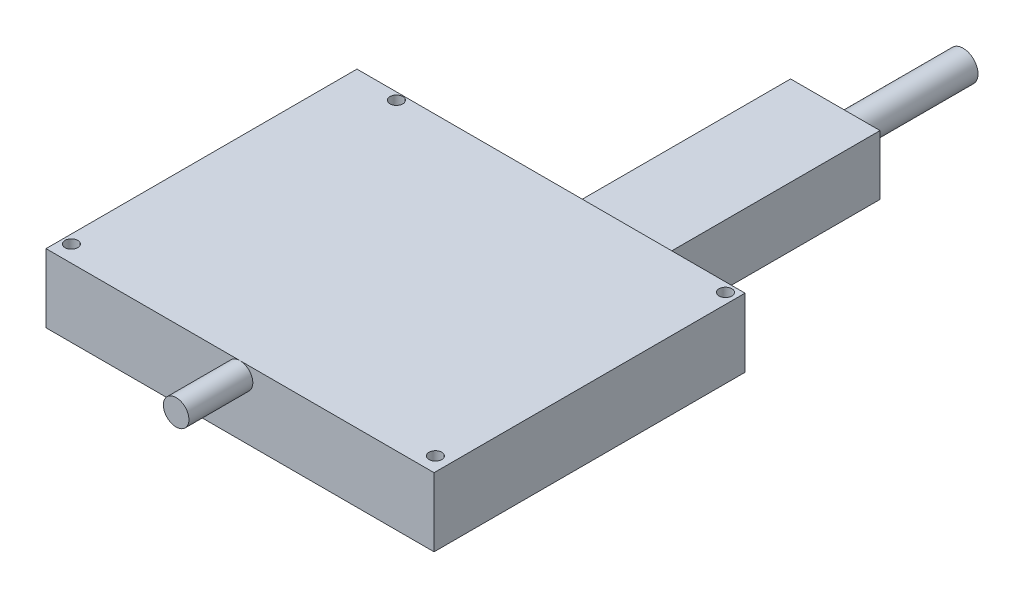
SolidWorks part; units mm, degrees
ref_plane "Front Plane" through (0, 0, 0) normal (0, 0, 1) x (1, 0, 0)
ref_plane "Top Plane" through (0, 0, 0) normal (0, 1, 0) x (1, 0, 0)
ref_plane "Right Plane" through (0, 0, 0) normal (1, 0, 0) x (0, 0, -1)
sketch "Sketch1" plane through (0, 0, 0) normal (0, 1, 0) x (1, 0, 0)
  line L1 (-45.55, 36.5) -> (45.55, 36.5)
  line L2 (-45.55, 36.5) -> (-45.55, -36.5)
  line L3 (-45.55, -36.5) -> (45.55, -36.5)
  line L4 (45.55, 36.5) -> (45.55, -36.5)
  line L5 (-45.55, 36.5) -> (45.55, -36.5) construction
  line L6 (-45.55, -36.5) -> (45.55, 36.5) construction
  circle A0 centre (-34.59, 34.8) radius 1.5
  circle A1 centre (43.1, 34.36) radius 1.5
  circle A2 centre (42.3, -32.93) radius 1.5
  circle A3 centre (-43.5, -32.58) radius 1.5
  point P0 (0, 0)
  point P14 (42.7339, 32.5203)
  dimension "D3" = 0.55
  dimension "D4" = 2.42
  dimension "D5" = 1.75
  dimension "D6" = 2.07
  dimension "D7" = 0.95
  dimension "D8" = 0.64
  dimension "D9" = 0.2
  dimension "D10" = 9.46
  dimension "D11" = 3
  dimension "D1" = 73
  dimension "D2" = 91.1
extrude "Boss-Extrude1" add sketch "Sketch1" along normal blind 16.1
sketch "Sketch2" plane through (0, 0, 36.5) normal (0, 0, 1) x (1, 0, 0)
  line L0 (-45.55, 16.1) -> (45.55, 16.1) construction
  circle A0 centre (0, 13.1) radius 3
  dimension "D1" = 6
extrude "Boss-Extrude2" add sketch "Sketch2" along normal blind 15
sketch "Sketch3" plane through (0, 0, 0) normal (0, 1, 0) x (1, 0, 0)
  line L0 (45.55, 36.5) -> (-45.55, 36.5) construction
  line L1 (3.25, 36.5) -> (24.25, 36.5)
  line L2 (3.25, 36.5) -> (3.25, 89.5)
  line L3 (3.25, 89.5) -> (24.25, 89.5)
  line L4 (24.25, 36.5) -> (24.25, 89.5)
  line L5 (45.55, -36.5) -> (45.55, 36.5) construction
  dimension "D1" = 53
  dimension "D2" = 21
  dimension "D3" = 21.3
extrude "Boss-Extrude3" add sketch "Sketch3" along normal blind 12 and the other way blind 2
sketch "Sketch4" plane through (0, 0, -89.5) normal (0, 0, -1) x (-1, 0, 0)
  line L1 (-3.25, 5) -> (-24.25, 5) construction
  line L2 (-3.25, -2) -> (-3.25, 12) construction
  line L3 (-24.25, 0) -> (-24.25, 12) construction
  circle A0 centre (-13.75, 5) radius 3.5
  dimension "D1" = 7
extrude "Boss-Extrude4" add sketch "Sketch4" along normal blind 30
